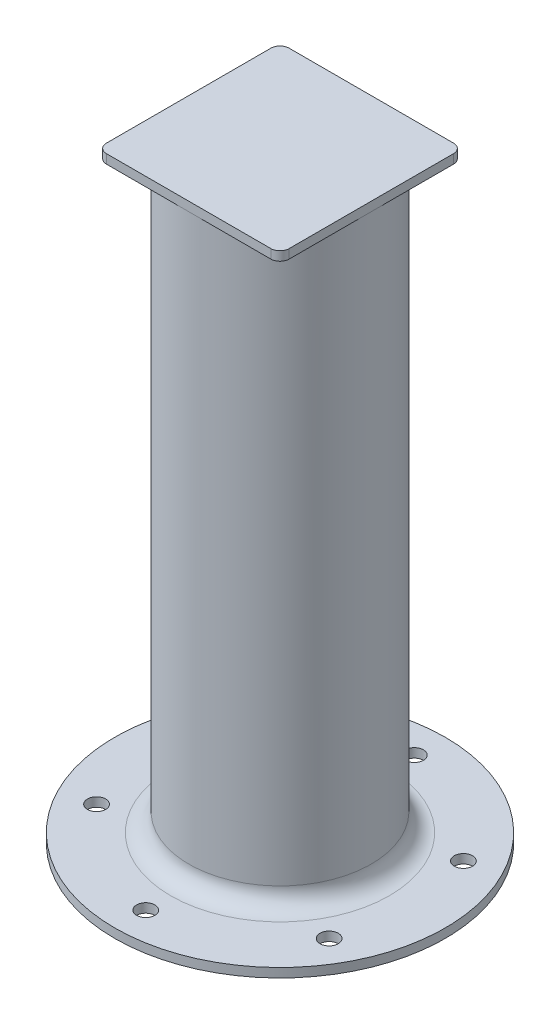
SolidWorks part; units mm, degrees
ref_plane "Front Plane" through (0, 0, 0) normal (0, 0, 1) x (1, 0, 0)
ref_plane "Top Plane" through (0, 0, 0) normal (0, 1, 0) x (1, 0, 0)
ref_plane "Right Plane" through (0, 0, 0) normal (1, 0, 0) x (0, 0, -1)
sketch "Sketch1" plane through (0, 0, 0) normal (0, 1, 0) x (1, 0, 0)
  circle A0 centre (0, 0) radius 100
  dimension "D1" = 200
extrude "Boss-Extrude1" add sketch "Sketch1" along normal mid plane 650
sketch "Sketch2" plane through (0, -325, 0) normal (0, -1, 0) x (1, 0, 0)
  circle A0 centre (0, 0) radius 181.2555
  circle A1 centre (0, 147.2918) radius 10
  circle A2 centre (127.5585, 73.6459) radius 10
  circle A3 centre (127.5585, -73.6459) radius 10
  circle A4 centre (0, -147.2918) radius 10
  circle A5 centre (-127.5585, -73.6459) radius 10
  circle A6 centre (-127.5585, 73.6459) radius 10
  point P18 (0, 0)
  dimension "D1" = 6
extrude "Boss-Extrude2" add sketch "Sketch2" along normal mid plane 10
fillet "Fillet1" radius 20 1 edges at (0, -320, -100)
sketch "Sketch3" plane through (0, 325, 0) normal (0, 1, 0) x (1, 0, 0)
  line L1 (-90.194, -100.194) -> (90.194, -100.194)
  line L2 (-100.194, -90.194) -> (-100.194, 90.194)
  line L3 (-90.194, 100.194) -> (90.194, 100.194)
  line L4 (100.194, -90.194) -> (100.194, 90.194)
  line L5 (-100.194, -100.194) -> (100.194, 100.194) construction
  line L6 (-100.194, 100.194) -> (100.194, -100.194) construction
  arc A0 (90.194, -100.194) -> (100.194, -90.194) centre (90.194, -90.194) ccw
  arc A1 (-100.194, 90.194) -> (-90.194, 100.194) centre (-90.194, 90.194) cw
  arc A2 (-90.194, -100.194) -> (-100.194, -90.194) centre (-90.194, -90.194) cw
  arc A3 (90.194, 100.194) -> (100.194, 90.194) centre (90.194, 90.194) cw
  point P0 (0, 0)
  dimension "D1" = 10
extrude "Boss-Extrude3" add sketch "Sketch3" along normal mid plane 10
